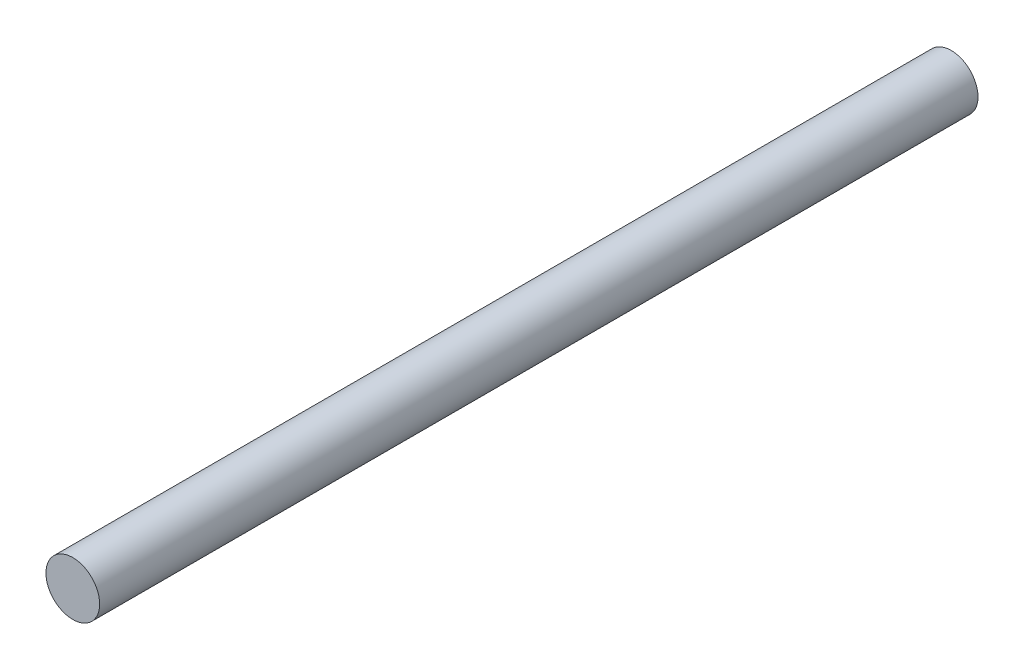
SolidWorks part; units mm, degrees
ref_plane "Front Plane" through (0, 0, 0) normal (0, 0, 1) x (1, 0, 0)
ref_plane "Top Plane" through (0, 0, 0) normal (0, 1, 0) x (1, 0, 0)
ref_plane "Right Plane" through (0, 0, 0) normal (1, 0, 0) x (0, 0, -1)
sketch "Sketch2" plane through (0, 0, 0) normal (0, 0, 1) x (1, 0, 0)
  circle A0 centre (0, 0) radius 3.175
extrude "Boss-Extrude1" add sketch "Sketch2" along normal blind 103.886
